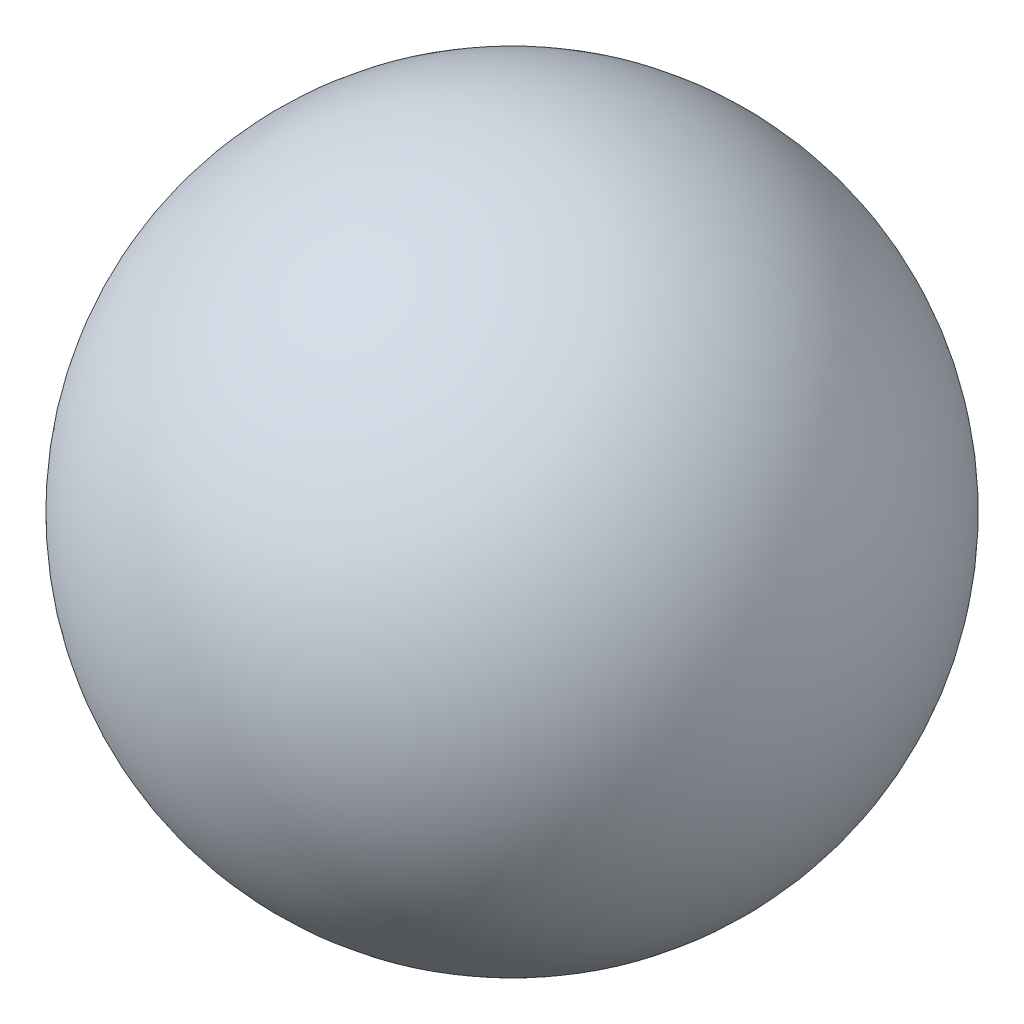
SolidWorks part; units mm, degrees
ref_plane "前视基准面" through (0, 0, 0) normal (0, 0, 1) x (1, 0, 0)
ref_plane "上视基准面" through (0, 0, 0) normal (0, 1, 0) x (1, 0, 0)
ref_plane "右视基准面" through (0, 0, 0) normal (1, 0, 0) x (0, 0, -1)
sketch "草图1" plane through (0, 0, 0) normal (0, 0, 1) x (1, 0, 0)
  line L0 (0, 128) -> (0, -128)
  arc A0 (0, 128) -> (0, -128) centre (0, 0) ccw
  dimension "D1" = 256
revolve "旋转1" add sketch "草图1" angle 360 about L0
